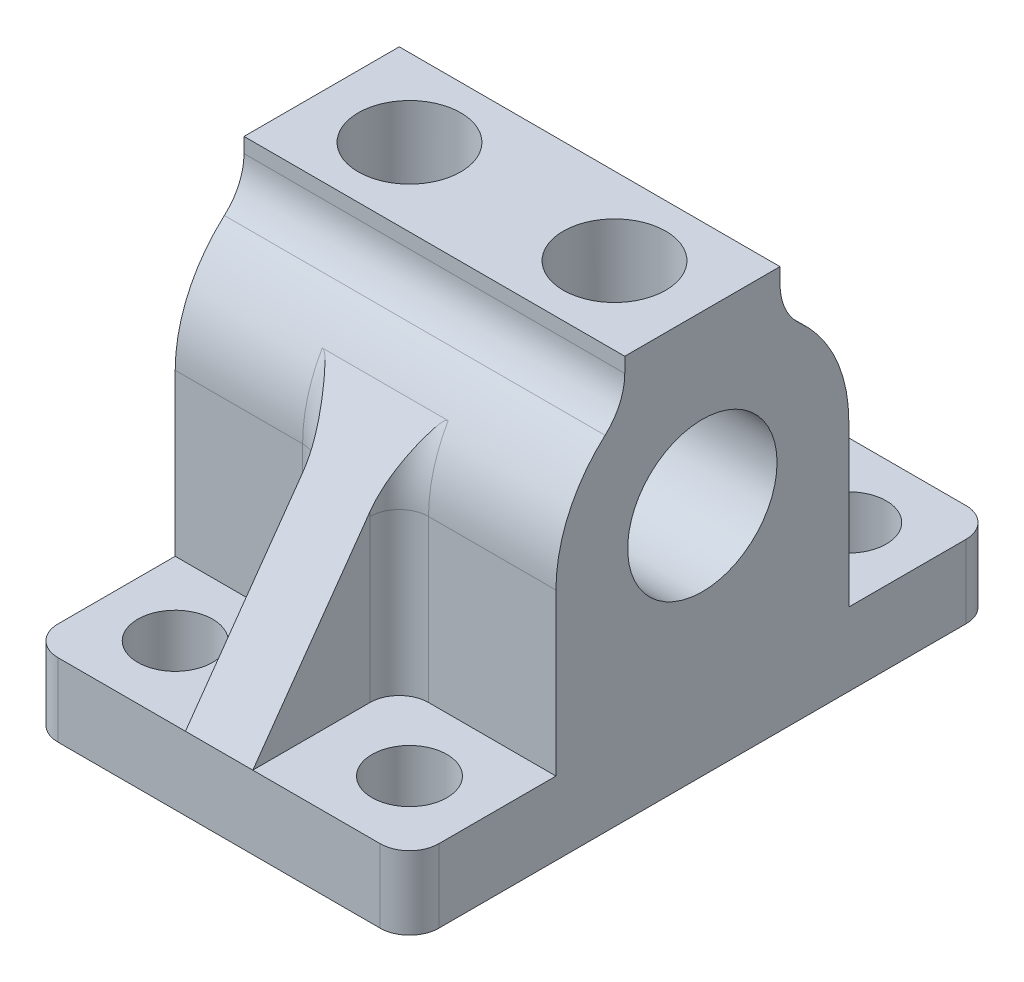
SolidWorks part; units mm, degrees
material "PLA2"
ref_plane "Front Plane" through (0, 0, 0) normal (0, 0, 1) x (1, 0, 0)
ref_plane "Top Plane" through (0, 0, 0) normal (0, 1, 0) x (1, 0, 0)
ref_plane "Right Plane" through (0, 0, 0) normal (1, 0, 0) x (0, 0, -1)
sketch "Sketch1" plane through (0, 0, 0) normal (1, 0, 0) x (0, 0, -1)
  line L0 (0, 0) -> (27506.0917, 0) construction
  line L1 (0.3138, 19.05) -> (27506.4055, 19.05) construction
  line L2 (0, 29.21) -> (0, 0) construction
  line L3 (12.7, 19.05) -> (-12.7, 19.05)
  line L4 (-12.7, 19.05) -> (-12.7, 22.225)
  line L5 (-12.7, 22.225) -> (-6.35, 22.225)
  line L6 (-6.35, 22.225) -> (-6.35, 29.21)
  line L7 (0, 29.21) -> (0, 35.56) construction
  line L8 (6.35, 22.225) -> (6.35, 29.21)
  line L9 (12.7, 22.225) -> (6.35, 22.225)
  line L10 (12.7, 19.05) -> (12.7, 22.225)
  circle A0 centre (0, 29.21) radius 3.2385
  arc A1 (6.35, 29.21) -> (-6.35, 29.21) centre (0, 29.21) ccw
  point P19 (0, 19.05)
  dimension "D2" = 6.477
  dimension "D4" = 12.7
  dimension "D7" = 3.1115
  dimension "D1" = 19.05
  dimension "D3" = 29.21
  dimension "D5" = 3.175
  dimension "D6" = 6.35
extrude "Boss-Extrude1" add sketch "Sketch1" along normal mid plane 16.51
sketch "Sketch2" plane through (0, 0, 0) normal (1, 0, 0) x (0, 0, -1)
  line L0 (0, 32.4485) -> (0, 25.9715) construction
  line L1 (-5.4993, 32.385) -> (-12.7, 22.225)
  line L2 (-6.35, 22.225) -> (-12.7, 22.225) construction
  line L3 (-12.7, 22.225) -> (-5.4993, 22.225)
  line L4 (-5.4993, 22.225) -> (-5.4993, 32.385)
  line L5 (5.4993, 22.225) -> (5.4993, 32.385)
  line L6 (12.7, 22.225) -> (5.4993, 22.225)
  line L7 (5.4993, 32.385) -> (12.7, 22.225)
  circle A0 centre (0, 29.21) radius 3.2385 construction
  arc A1 (6.35, 29.21) -> (-6.35, 29.21) centre (0, 29.21) ccw construction
  dimension "D1" = 10.16
extrude "Boss-Extrude2" add sketch "Sketch2" along normal mid plane 2.921
sketch "Sketch3" plane through (0, 22.225, 0) normal (0, 1, 0) x (1, 0, 0)
  line L0 (-8.255, 0) -> (8.255, 0) construction
  line L1 (-8.255, 6.35) -> (-8.255, -6.35) construction
  line L2 (8.255, -6.35) -> (8.255, 6.35) construction
  line L3 (0, 12.7) -> (0, -12.7) construction
  line L4 (1.4605, 12.7) -> (-1.4605, 12.7) construction
  line L5 (1.4605, -12.7) -> (-1.4605, -12.7) construction
  circle A0 centre (-5.08, 9.525) radius 1.6256
  circle A1 centre (5.08, 9.525) radius 1.6256
  circle A2 centre (5.08, -9.525) radius 1.6256
  circle A3 centre (-5.08, -9.525) radius 1.6256
  dimension "D1" = 3.2512
  dimension "D2" = 10.16
  dimension "D3" = 19.05
extrude "Cut-Extrude1" cut sketch "Sketch3" against normal through all
sketch "Sketch4" plane through (8.255, 0, 0) normal (1, 0, 0) x (0, 0, -1)
  line L0 (3.3655, 34.5948) -> (-3.3655, 34.5948)
  arc A0 (6.35, 29.21) -> (-6.35, 29.21) centre (0, 29.21) ccw construction
  arc A1 (3.3655, 34.5948) -> (-3.3655, 34.5948) centre (0, 29.21) ccw
  dimension "D1" = 6.731
extrude "Cut-Extrude2" cut sketch "Sketch4" against normal through all
sketch "Sketch6" plane through (0, 34.5948, 0) normal (0, 1, 0) x (1, 0, 0)
  line L4 (8.255, -3.3655) -> (8.255, 3.3655)
  line L5 (8.255, 3.3655) -> (-8.255, 3.3655)
  line L6 (-8.255, 3.3655) -> (-8.255, -3.3655)
  line L7 (-8.255, -3.3655) -> (8.255, -3.3655)
  line L8 (8.255, -3.3655) -> (8.255, 3.3655)
  line L9 (8.255, 3.3655) -> (-8.255, 3.3655)
  line L10 (-8.255, 3.3655) -> (-8.255, -3.3655)
  line L11 (-8.255, -3.3655) -> (8.255, -3.3655)
  dimension "D1" = 0
extrude "Boss-Extrude3" add sketch "Sketch6" along normal blind 1.905
sketch "Sketch5" plane through (0, 36.4998, 0) normal (0, 1, 0) x (1, 0, 0)
  line L0 (0, 12.7) -> (0, -12.7) construction
  line L1 (1.4605, 12.7) -> (-1.4605, 12.7) construction
  line L2 (1.4605, -12.7) -> (-1.4605, -12.7) construction
  line L3 (-8.255, 0) -> (8.255, 0) construction
  line L6 (-8.255, 3.3655) -> (-8.255, -3.3655) construction
  line L7 (8.255, -3.3655) -> (8.255, 3.3655) construction
  circle A0 centre (-4.445, 0) radius 2.2225
  circle A1 centre (4.445, 0) radius 2.2225
  point P8 (0, 0)
  point P11 (0, 0)
  dimension "D1" = 4.445
  dimension "D2" = 8.89
extrude "Cut-Extrude3" cut sketch "Sketch5" against normal blind 6.35
fillet "Fillet1" radius 1.27 12 edges at (-1.4605, 30.8535, 6.1336) (1.4605, 30.8535, 6.1336) (-1.4605, 30.8535, -6.1336) (1.4605, 30.8535, -6.1336) (-1.4605, 25.7175, 6.35) (1.4605, 25.7175, 6.35) (-1.4605, 25.7175, -6.35) (1.4605, 25.7175, -6.35) (-8.255, 20.6375, -12.7) (8.255, 20.6375, -12.7) (-8.255, 20.6375, 12.7) (8.255, 20.6375, 12.7)
fillet "Fillet2" radius 2.54 2 edges at (0, 34.5948, -3.3655) (0, 34.5948, 3.3655)
